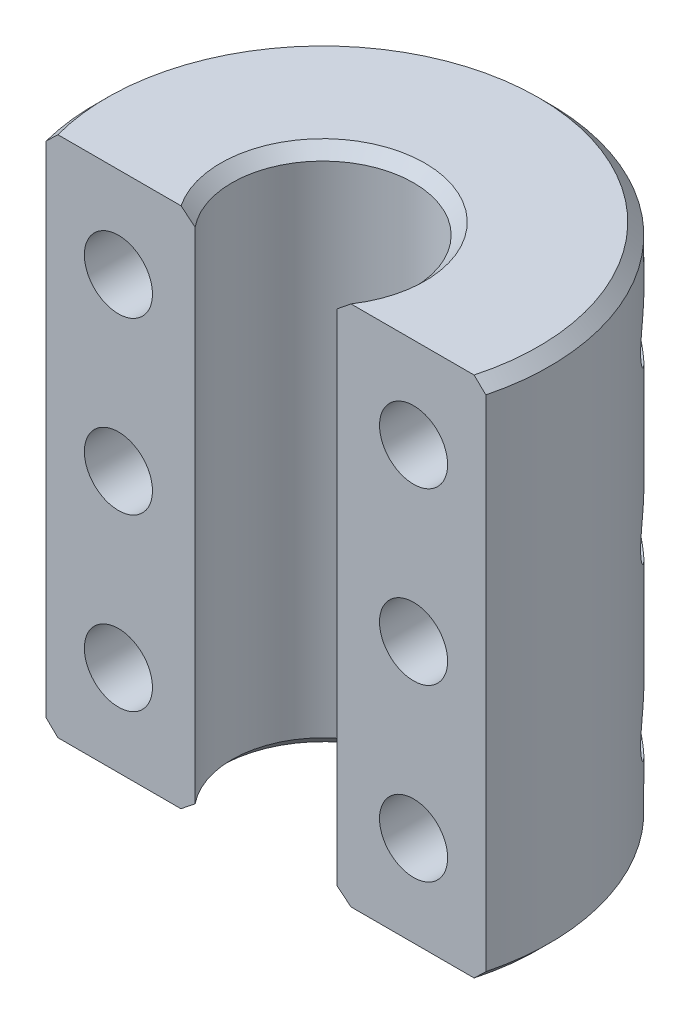
SolidWorks part; units mm, degrees
ref_plane "前视基准面" through (0, 0, 0) normal (0, 0, 1) x (1, 0, 0)
ref_plane "上视基准面" through (0, 0, 0) normal (0, 1, 0) x (1, 0, 0)
ref_plane "右视基准面" through (0, 0, 0) normal (1, 0, 0) x (0, 0, -1)
sketch "草图1" plane through (0, 0, 0) normal (0, 1, 0) x (1, 0, 0)
  circle A0 centre (0, 0) radius 4
  circle A1 centre (0, 0) radius 10
  dimension "D1" = 20
  dimension "D2" = 8
extrude "凸台-拉伸1" add sketch "草图1" along normal blind 23
chamfer "倒角1" distance 0.5 angle 45 4 edges at (0, 0, 4) (0, 0, 10) (0, 23, 10) (0, 23, 4)
ref_plane "基准面1" through (0, 0, 2.5) normal (0, 0, 1) x (1, 0, 0)
sketch "草图2" plane through (0, 0, 2.5) normal (0, 0, 1) x (1, 0, 0)
  line L0 (-10, 0) -> (10, 0)
  line L1 (10, 0) -> (10, 23)
  line L2 (10, 23) -> (-10, 23)
  line L3 (4.5, 23) -> (-4.5, 23) construction
  line L4 (0, 23) -> (0, 0) construction
  line L5 (-10, 0) -> (-10, 23)
extrude "切除-拉伸1" cut sketch "草图2" along normal blind 23
sketch "草图3" plane through (0, 0, 2.5) normal (0, 0, 1) x (1, 0, 0)
  line L0 (-9.6825, 11.5) -> (9.6825, 11.5) construction
  line L1 (-9.6825, 22.5) -> (-9.6825, 0.5) construction
  line L2 (9.6825, 0.5) -> (9.6825, 22.5) construction
  line L3 (-6.5, 11.5) -> (-6.5, 4) construction
  line L4 (0, 0) -> (0, 23) construction
  line L5 (4.5, 23) -> (-4.5, 23) construction
  line L6 (6.5, 11.5) -> (6.5, 4) construction
  circle A0 centre (-6.5, 11.5) radius 1.5
  circle A1 centre (-6.5, 4) radius 1.5
  circle A2 centre (-6.5, 19) radius 1.5
  circle A3 centre (6.5, 19) radius 1.5
  circle A4 centre (6.5, 4) radius 1.5
  circle A5 centre (6.5, 11.5) radius 1.5
  dimension "D1" = 3
  dimension "D2" = 3
  dimension "D3" = 13
  dimension "D4" = 15
extrude "切除-拉伸2" cut sketch "草图3" against normal through all
